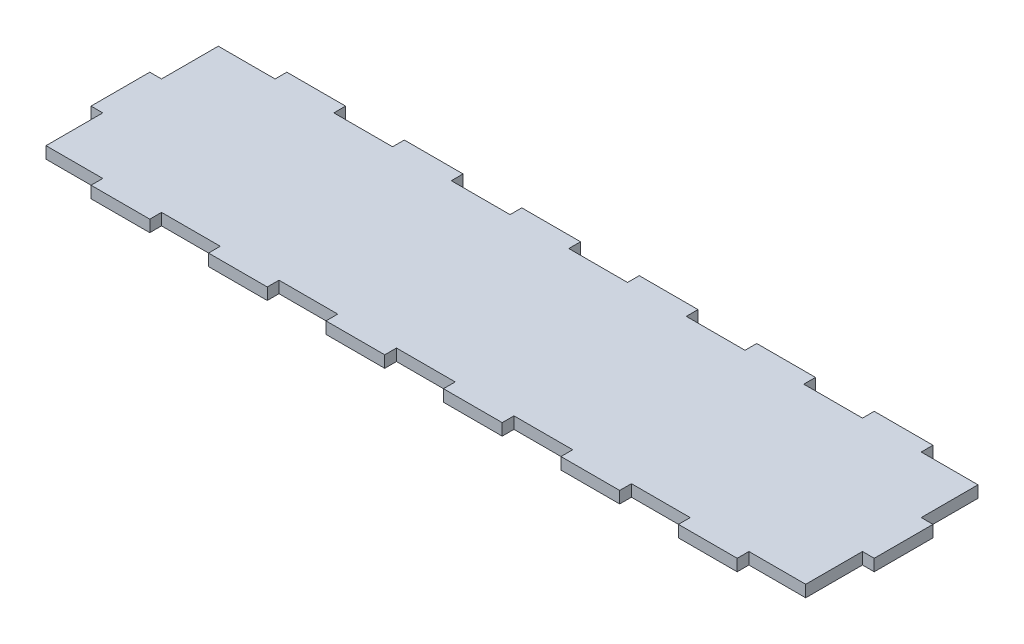
SolidWorks part; units mm, degrees
ref_plane "Alzado" through (0, 0, 0) normal (0, 0, 1) x (1, 0, 0)
ref_plane "Planta" through (0, 0, 0) normal (0, 1, 0) x (1, 0, 0)
ref_plane "Vista lateral" through (0, 0, 0) normal (1, 0, 0) x (0, 0, -1)
sketch "Croquis1" plane through (0, 0, 0) normal (0, 1, 0) x (1, 0, 0)
  line L1 (200, 17.5) -> (200, 32.5)
  line L2 (182.5, 50) -> (167.5, 50)
  line L3 (0, 32.5) -> (0, 17.5)
  line L4 (0, 25) -> (0, 32.5)
  line L5 (0, 32.5) -> (3, 32.5)
  line L6 (3, 32.5) -> (3, 47)
  line L7 (137.5, 0) -> (152.5, 0)
  line L8 (107.5, 47) -> (92.5, 47)
  line L9 (92.5, 47) -> (92.5, 50)
  line L10 (92.5, 50) -> (77.5, 50)
  line L11 (77.5, 50) -> (77.5, 47)
  line L12 (77.5, 47) -> (62.5, 47)
  line L13 (62.5, 47) -> (62.5, 50)
  line L14 (62.5, 50) -> (47.5, 50)
  line L15 (47.5, 50) -> (47.5, 47)
  line L16 (47.5, 47) -> (32.5, 47)
  line L17 (32.5, 47) -> (32.5, 50)
  line L18 (32.5, 50) -> (17.5, 50)
  line L19 (17.5, 50) -> (17.5, 47)
  line L20 (17.5, 47) -> (3, 47)
  line L21 (182.5, 47) -> (197, 47)
  line L22 (182.5, 50) -> (182.5, 47)
  line L23 (167.5, 47) -> (167.5, 50)
  line L24 (152.5, 47) -> (167.5, 47)
  line L25 (152.5, 50) -> (152.5, 47)
  line L26 (137.5, 47) -> (137.5, 50)
  line L27 (122.5, 47) -> (137.5, 47)
  line L28 (122.5, 50) -> (122.5, 47)
  line L29 (107.5, 47) -> (107.5, 50)
  line L30 (197, 32.5) -> (197, 47)
  line L31 (200, 32.5) -> (197, 32.5)
  line L32 (17.5, 0) -> (32.5, 0)
  line L33 (200, 17.5) -> (197, 17.5)
  line L34 (197, 17.5) -> (197, 3)
  line L35 (107.5, 3) -> (107.5, 0)
  line L36 (122.5, 0) -> (122.5, 3)
  line L37 (122.5, 3) -> (137.5, 3)
  line L38 (137.5, 3) -> (137.5, 0)
  line L39 (152.5, 0) -> (152.5, 3)
  line L40 (152.5, 3) -> (167.5, 3)
  line L41 (167.5, 3) -> (167.5, 0)
  line L42 (182.5, 0) -> (182.5, 3)
  line L43 (182.5, 3) -> (197, 3)
  line L44 (17.5, 3) -> (3, 3)
  line L45 (17.5, 0) -> (17.5, 3)
  line L46 (32.5, 3) -> (32.5, 0)
  line L47 (47.5, 3) -> (32.5, 3)
  line L48 (47.5, 0) -> (47.5, 3)
  line L49 (62.5, 3) -> (62.5, 0)
  line L50 (77.5, 3) -> (62.5, 3)
  line L51 (77.5, 0) -> (77.5, 3)
  line L52 (92.5, 3) -> (92.5, 0)
  line L53 (107.5, 3) -> (92.5, 3)
  line L55 (3, 17.5) -> (3, 3)
  line L56 (0, 17.5) -> (3, 17.5)
  line L57 (32.5, 50) -> (17.5, 50)
  line L58 (62.5, 50) -> (47.5, 50)
  line L59 (92.5, 50) -> (77.5, 50)
  line L60 (122.5, 50) -> (107.5, 50)
  line L61 (152.5, 50) -> (137.5, 50)
  line L62 (47.5, 0) -> (62.5, 0)
  line L63 (77.5, 0) -> (92.5, 0)
  line L64 (107.5, 0) -> (122.5, 0)
  line L65 (167.5, 0) -> (182.5, 0)
  dimension "D3" = 7.5
  dimension "D4" = 3
  dimension "D7" = 15
  dimension "D8" = 15
  dimension "D9" = 15
  dimension "D10" = 15
  dimension "D11" = 15
extrude "Saliente-Extruir1" add sketch "Croquis1" along normal blind 3 contours L41 L65 L42 L43 L34 L33 L1 L31 L30 L21 L22 L2 L23 L24 L25 L61 L26 L27 L28 L60 L29 L8 L9 L10 L11 L12 L13 L14 L15 L16 L17 L18 L19 L20 L6 L5 L3 L56 L55 L44 L45 L32 L46 L47 L48 L62 L49 L50 L51 L63
